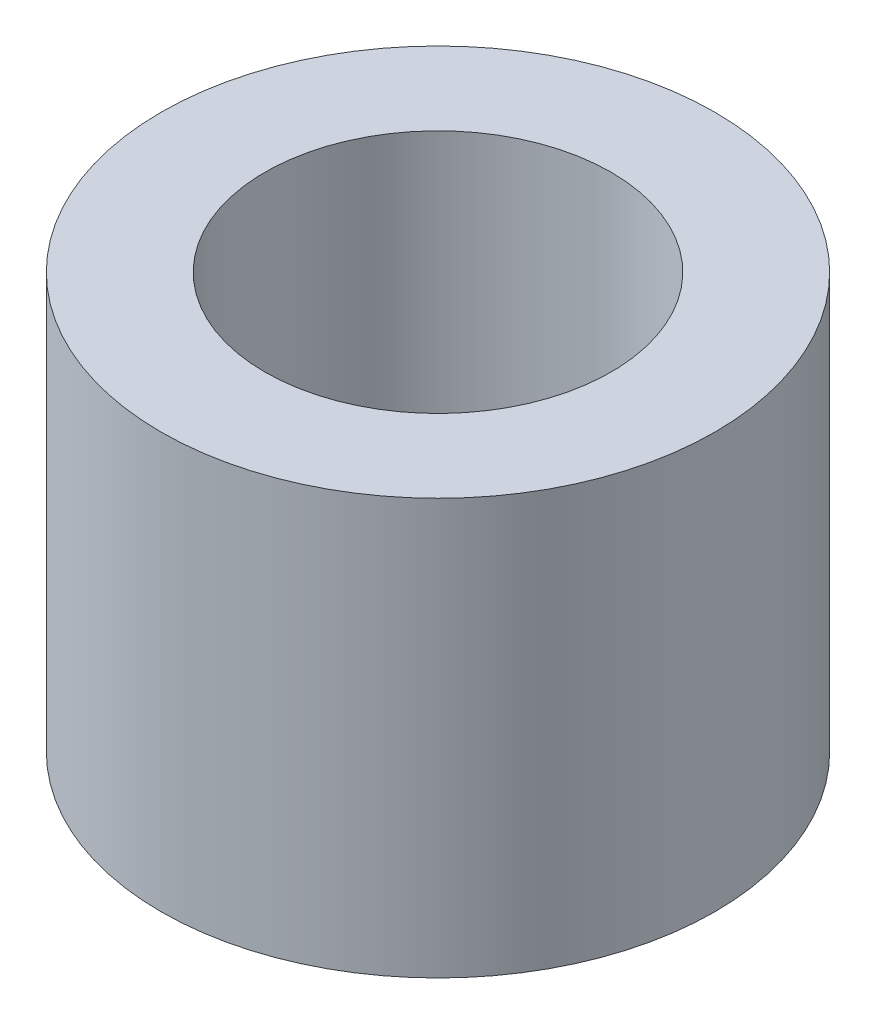
SolidWorks part; units mm, degrees
ref_plane "Front Plane" through (0, 0, 0) normal (0, 0, 1) x (1, 0, 0)
ref_plane "Top Plane" through (0, 0, 0) normal (0, 1, 0) x (1, 0, 0)
ref_plane "Right Plane" through (0, 0, 0) normal (1, 0, 0) x (0, 0, -1)
sketch "Sketch1" plane through (0, 0, 0) normal (0, 0, 1) x (1, 0, 0)
  line L0 (-8, 7.1619) -> (-8, -4.8381)
  line L1 (-8, -4.8381) -> (-5, -4.8381)
  line L2 (-5, -4.8381) -> (-5, 7.1619)
  line L3 (-5, 7.1619) -> (-8, 7.1619)
  line L4 (0, 10.4762) -> (0, -12.8762) construction
  dimension "D1" = 12
  dimension "D2" = 3
  dimension "D3" = 5
revolve "Revolve1" add sketch "Sketch1" angle 360 about L4
